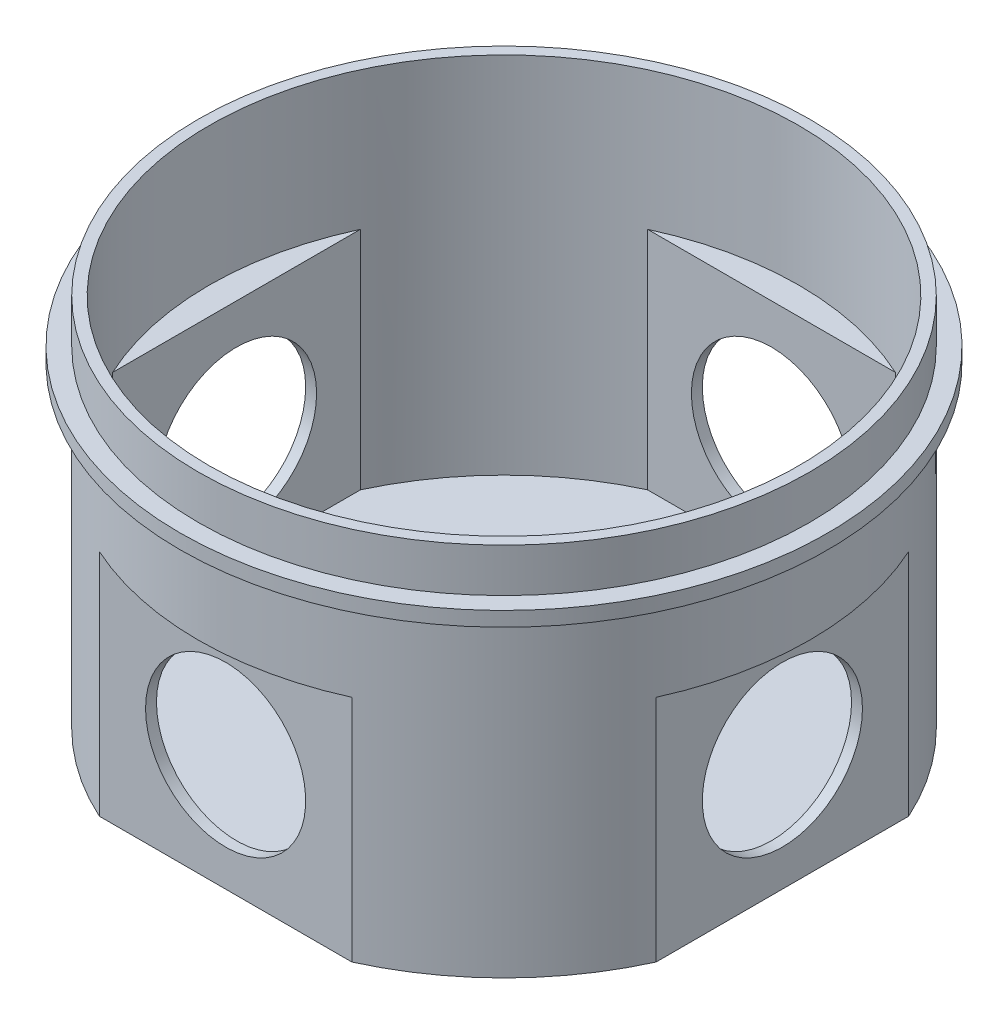
SolidWorks part; units mm, degrees
ref_plane "Спереди" through (0, 0, 0) normal (0, 0, 1) x (1, 0, 0)
ref_plane "Сверху" through (0, 0, 0) normal (0, 1, 0) x (1, 0, 0)
ref_plane "Справа" through (0, 0, 0) normal (1, 0, 0) x (0, 0, -1)
sketch "Эскиз1" plane through (0, 0, 0) normal (0, 1, 0) x (1, 0, 0)
  line L0 (0, 0) -> (0, 38.25) construction
  line L1 (-38.25, 38.25) -> (38.25, 38.25)
  line L2 (-38.25, 38.25) -> (-38.25, -38.25)
  line L3 (-38.25, -38.25) -> (38.25, -38.25)
  line L4 (38.25, 38.25) -> (38.25, -38.25)
  line L5 (0, 0) -> (38.25, 0) construction
  circle A0 centre (0, 0) radius 42
  point P7 (0, -0.5947)
  dimension "D1" = 84
  dimension "D2" = 76.5
extrude "Бобышка-Вытянуть1" add sketch "Эскиз1" along normal blind 1.5 contours L3 A0 L4 L1 L2
sketch "Эскиз2" plane through (0, 1.5, 0) normal (0, 1, 0) x (1, 0, 0)
  line L4 (-17.0202, -36.75) -> (17.0202, -36.75)
  line L5 (36.75, -17.0202) -> (36.75, 17.0202)
  line L6 (17.0202, 36.75) -> (-17.0202, 36.75)
  line L7 (-36.75, 17.0202) -> (-36.75, -17.0202)
  line L8 (-17.3476, -38.25) -> (17.3476, -38.25)
  line L9 (38.25, -17.3476) -> (38.25, 17.3476)
  line L10 (17.3476, 38.25) -> (-17.3476, 38.25)
  line L11 (-38.25, 17.3476) -> (-38.25, -17.3476)
  line L12 (-17.3476, -38.25) -> (17.3476, -38.25)
  line L13 (38.25, -17.3476) -> (38.25, 17.3476)
  line L14 (17.3476, 38.25) -> (-17.3476, 38.25)
  line L15 (-38.25, 17.3476) -> (-38.25, -17.3476)
  arc A4 (17.0202, -36.75) -> (36.75, -17.0202) centre (0, 0) ccw
  arc A5 (36.75, 17.0202) -> (17.0202, 36.75) centre (0, 0) ccw
  arc A6 (-17.0202, 36.75) -> (-36.75, 17.0202) centre (0, 0) ccw
  arc A7 (-36.75, -17.0202) -> (-17.0202, -36.75) centre (0, 0) ccw
  arc A8 (17.3476, -38.25) -> (38.25, -17.3476) centre (0, 0) ccw
  arc A9 (38.25, 17.3476) -> (17.3476, 38.25) centre (0, 0) ccw
  arc A10 (-17.3476, 38.25) -> (-38.25, 17.3476) centre (0, 0) ccw
  arc A11 (-38.25, -17.3476) -> (-17.3476, -38.25) centre (0, 0) ccw
  arc A12 (17.3476, -38.25) -> (38.25, -17.3476) centre (0, 0) ccw
  arc A13 (38.25, 17.3476) -> (17.3476, 38.25) centre (0, 0) ccw
  arc A14 (-17.3476, 38.25) -> (-38.25, 17.3476) centre (0, 0) ccw
  arc A15 (-38.25, -17.3476) -> (-17.3476, -38.25) centre (0, 0) ccw
  dimension "D1" = 0
  dimension "D2" = 1.5
extrude "Бобышка-Вытянуть2" add sketch "Эскиз2" along normal blind 30
sketch "Эскиз3" plane through (0, 31.5, 0) normal (0, 1, 0) x (1, 0, 0)
  circle A0 centre (0, 0) radius 42
  circle A1 centre (0, 0) radius 40.5
  arc M1 (-38.25, -17.3476) -> (-17.3476, -38.25) centre (0, 0) ccw
  line M2 (-17.3476, -38.25) -> (17.3476, -38.25)
  arc M3 (17.3476, -38.25) -> (38.25, -17.3476) centre (0, 0) ccw
  line M4 (38.25, -17.3476) -> (38.25, 17.3476)
  arc M5 (38.25, 17.3476) -> (17.3476, 38.25) centre (0, 0) ccw
  line M6 (17.3476, 38.25) -> (-17.3476, 38.25)
  arc M7 (-17.3476, 38.25) -> (-38.25, 17.3476) centre (0, 0) ccw
  line M8 (-38.25, 17.3476) -> (-38.25, -17.3476)
  line M9 (17.0202, -36.75) -> (-17.0202, -36.75)
  arc M10 (-17.0202, -36.75) -> (-36.75, -17.0202) centre (0, 0) cw
  line M11 (-36.75, -17.0202) -> (-36.75, 17.0202)
  arc M12 (-36.75, 17.0202) -> (-17.0202, 36.75) centre (0, 0) cw
  line M13 (-17.0202, 36.75) -> (17.0202, 36.75)
  arc M14 (17.0202, 36.75) -> (36.75, 17.0202) centre (0, 0) cw
  line M15 (36.75, 17.0202) -> (36.75, -17.0202)
  arc M16 (36.75, -17.0202) -> (17.0202, -36.75) centre (0, 0) cw
extrude "Бобышка-Вытянуть3" add sketch "Эскиз3" along normal blind 1 contours A1 M8 | A1 M11 M8 | A1 A0 M4 | A1 M4 | A1 M15 M4 | A1 M13 M6 | A1 M6 | A1 A0 M6 | A1 A0 M2 | A1 M2 | A1 M2 M9 | A1 M8 M1 M2 M10 | A1 M2 M3 M4 M16 | A1 M4 M5 M6 M14 | A1 M6 M7 M8 M12 | A1 A0 M8
sketch "Эскиз4" plane through (0, 32.5, 0) normal (0, 1, 0) x (1, 0, 0)
  circle A0 centre (0, 0) radius 42
  circle A1 centre (0, 0) radius 40.5
  circle A2 centre (0, 0) radius 42 construction
extrude "Бобышка-Вытянуть4" add sketch "Эскиз4" along normal blind 11
sketch "Эскиз5" plane through (0, 43.5, 0) normal (0, 1, 0) x (1, 0, 0)
  circle A0 centre (0, 0) radius 40.5 construction
  circle A1 centre (0, 0) radius 40.5
  circle A2 centre (0, 0) radius 44.5
  dimension "D1" = 89
extrude "Бобышка-Вытянуть5" add sketch "Эскиз5" along normal blind 2
sketch "Эскиз6" plane through (0, 45.5, 0) normal (0, 1, 0) x (1, 0, 0)
  circle A0 centre (0, 0) radius 42
  circle A1 centre (0, 0) radius 40.5 construction
  circle A2 centre (0, 0) radius 40.5
  dimension "D1" = 1.5
extrude "Бобышка-Вытянуть6" add sketch "Эскиз6" along normal blind 6
sketch "Эскиз7" plane through (38.25, 0, 0) normal (1, 0, 0) x (0, 0, -1)
  circle A0 centre (0, 16) radius 11
  point P2 (0, 5)
  point P4 (-2.0705, 15.5512)
  dimension "D1" = 22
  dimension "D2" = 5
extrude "Вырез-Вытянуть1" cut sketch "Эскиз7" against normal through all
pattern_circular "Круговой массив1" count 2 every 90 of "Вырез-Вытянуть1"
